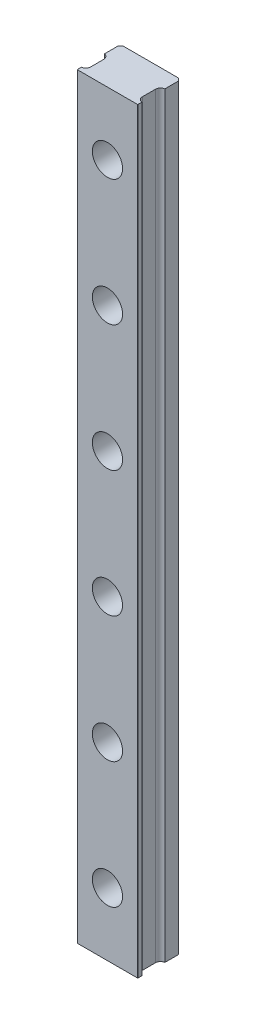
SolidWorks part; units mm, degrees
material "Aleación 1060"
ref_plane "Alzado" through (0, 0, 0) normal (0, 0, 1) x (1, 0, 0)
ref_plane "Planta" through (0, 0, 0) normal (0, 1, 0) x (1, 0, 0)
ref_plane "Vista lateral" through (0, 0, 0) normal (1, 0, 0) x (0, 0, -1)
ref_plane "Plano1" through (0, 0, 0) normal (0, 0, -1) x (-1, 0, 0)
sketch "Croquis1" plane through (0, 0, 0) normal (0, 0, -1) x (-1, 0, 0)
  line L0 (-6, 0) -> (6, 0)
  line L1 (6, 0) -> (6, 150)
  line L2 (6, 150) -> (-6, 150)
  line L3 (-6, 150) -> (-6, 0)
extrude "Saliente-Extruir1" add sketch "Croquis1" against normal blind 8.6
sketch "Croquis2" plane through (0, 0, 0) normal (0, -1, 0) x (1, 0, 0)
  line L0 (-6, 7.7922) -> (-6, 3.2078)
  line L1 (-5.125, 4.2) -> (-5.125, 6.8)
  arc A0 (-6, 3.2078) -> (-5.125, 4.2) centre (-6.125, 4.2) ccw
  arc A1 (-5.125, 6.8) -> (-6, 7.7922) centre (-6.125, 6.8) ccw
extrude "Cortar-Extruir1" cut sketch "Croquis2" against normal through all
sketch "Croquis3" plane through (0, 0, 0) normal (0, -1, 0) x (1, 0, 0)
  line L0 (6, 3.2078) -> (6, 7.7922)
  line L1 (5.125, 6.8) -> (5.125, 4.2)
  arc A0 (6, 7.7922) -> (5.125, 6.8) centre (6.125, 6.8) ccw
  arc A1 (5.125, 4.2) -> (6, 3.2078) centre (6.125, 4.2) ccw
extrude "Cortar-Extruir2" cut sketch "Croquis3" against normal through all
hole_wizard "Refrentado para tornillo con cabeza hexagonal de M31" positions "Croquis5" profile "Croquis4" counterbore size "M3" standard "Ansi Metric"
sketch "Croquis5" plane through (0, 0, 8.6) normal (0, 0, 1) x (1, 0, 0)
  point P0 (0, 137.5)
  point P1 (0, 112.5)
  point P2 (0, 87.5)
  point P3 (0, 62.5)
  point P4 (0, 37.5)
  point P5 (0, 12.5)
sketch "Croquis4" plane through (0, 137.5, 8.6) normal (1, 0, 0) x (0, -1, 0)
  line L0 (0, 0) -> (0, 8.6)
  line L1 (0, 8.6) -> (1.7, 8.6)
  line L3 (1.7, 8.6) -> (1.7, 5.6)
  line L4 (1.7, 5.6) -> (3, 5.6)
  line L5 (3, 5.6) -> (3, 0)
  line L7 (3, 0) -> (0, 0)
  line L11 (0, -6.35) -> (0, 107.95) construction
  dimension "Diámetro de taladro hasta el siguiente" = 3.4
  dimension "Profundidad de taladro hasta el siguiente" = 8.6
  dimension "Diámetro de refrentado" = 6
  dimension "Profundidad de refrentado" = 5.6
chamfer "Chaflán1" distance 0.05 angle 45 2 edges at (-6, 75, 8.6) (6, 75, 8.6)
chamfer "Chaflán2" distance 0.5 angle 45 2 edges at (-6, 75, 0) (6, 75, 0)
sketch "Croquis6" plane through (0, 0, 0) normal (0, 0, -1) x (-1, 0, 0)
  circle A0 centre (0, 137.5) radius 1.7
sketch "Croquis7" plane through (0, 150, 0) normal (0, 1, 0) x (1, 0, 0)
  line L0 (0, 0) -> (0, -8.6) construction
  line L1 (-5.95, -8.6) -> (5.95, -8.6) construction
sketch "Croquis8" plane through (0, 0, 8.6) normal (0, 0, 1) x (1, 0, 0)
  circle A0 centre (0, 137.5) radius 3
sketch "Croquis9" plane through (0, 0, 0) normal (0, 0, -1) x (-1, 0, 0)
  circle A0 centre (0, 112.5) radius 1.7
